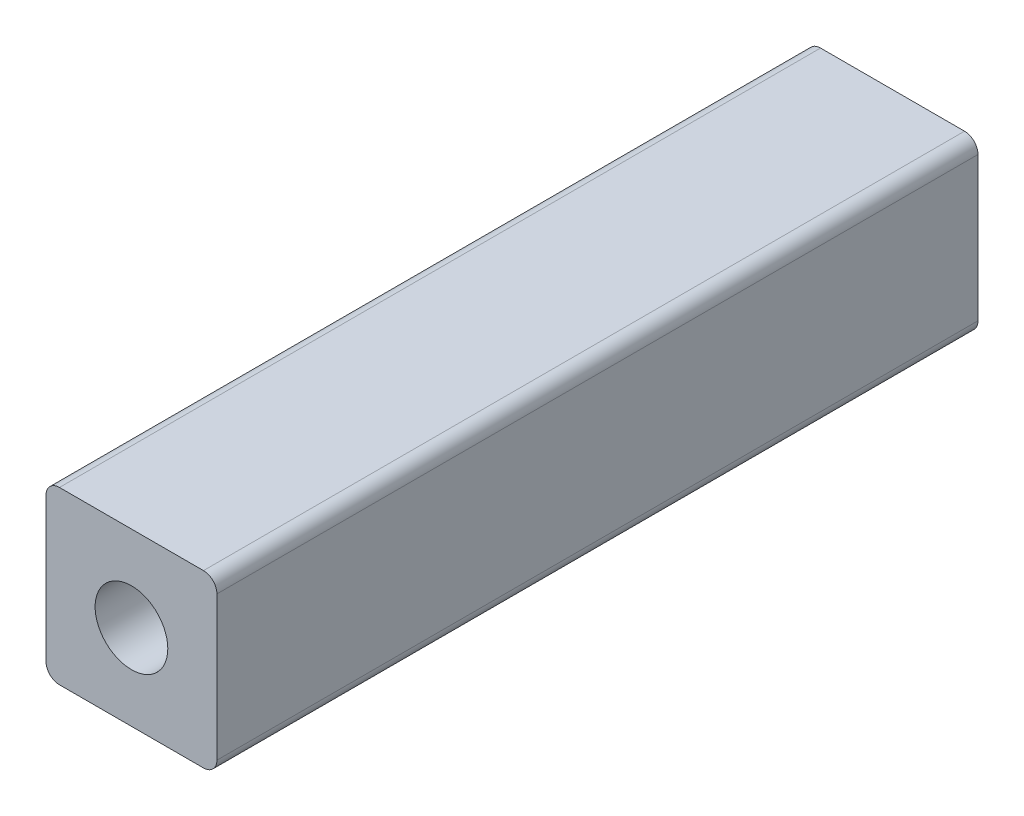
SolidWorks part; units mm, degrees
material "ABS"
ref_plane "X-Y Datum" through (0, 0, 0) normal (0, 0, 1) x (1, 0, 0)
ref_plane "X-Z Datum" through (0, 0, 0) normal (0, 1, 0) x (1, 0, 0)
ref_plane "Y-Z Datum" through (0, 0, 0) normal (1, 0, 0) x (0, 0, -1)
sketch "Sketch1" plane through (0, 0, 0) normal (0, 0, 1) x (1, 0, 0)
  line L1 (-6.35, 6.35) -> (6.35, 6.35)
  line L2 (-6.35, 6.35) -> (-6.35, -6.35)
  line L3 (-6.35, -6.35) -> (6.35, -6.35)
  line L4 (6.35, 6.35) -> (6.35, -6.35)
  line L5 (-6.35, 6.35) -> (6.35, -6.35) construction
  line L6 (-6.35, -6.35) -> (6.35, 6.35) construction
  circle A0 centre (0, 0) radius 2.7
  point P0 (0, 0)
  dimension "D1" = 5.4
  dimension "D2" = 12.7
  dimension "D3" = 12.7
extrude "Boss-Extrude1" add sketch "Sketch1" along normal mid plane 56.55
fillet "Fillet2" radius 1 4 edges at (-6.35, -6.35, 0) (-6.35, 6.35, 0) (6.35, 6.35, 0) (6.35, -6.35, 0)
